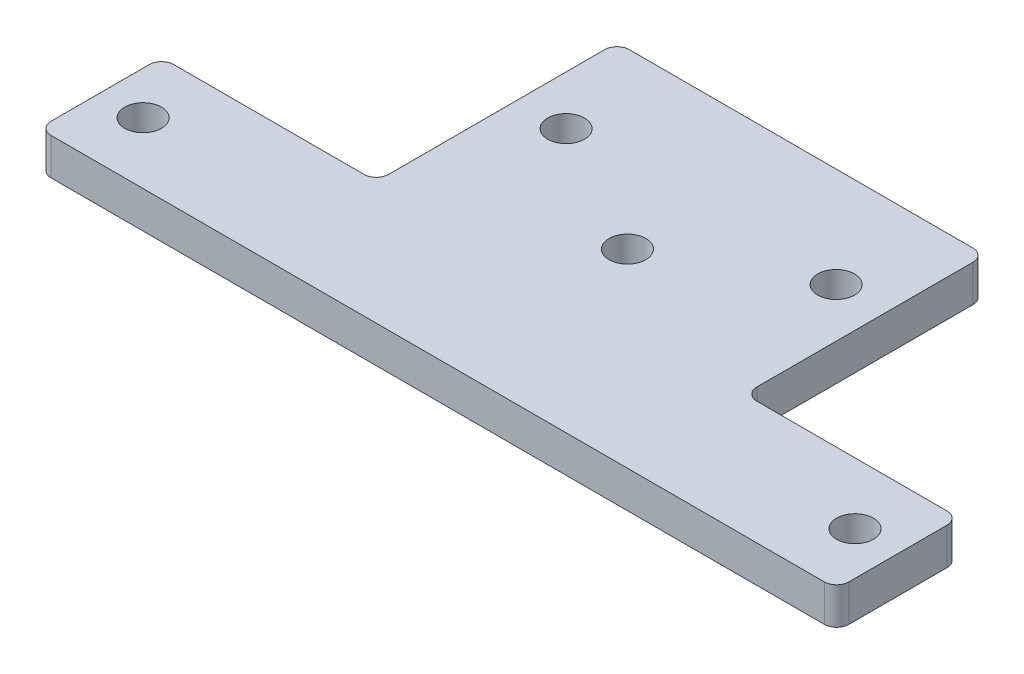
SolidWorks part; units mm, degrees
ref_plane "Alzado" through (0, 0, 0) normal (0, 0, 1) x (1, 0, 0)
ref_plane "Planta" through (0, 0, 0) normal (0, 1, 0) x (1, 0, 0)
ref_plane "Vista lateral" through (0, 0, 0) normal (1, 0, 0) x (0, 0, -1)
sketch "Croquis1" plane through (0, 0, 0) normal (0, 1, 0) x (1, 0, 0)
  line L0 (32.8028, -15.0723) -> (32.8028, -5.0723)
  line L1 (-32.1972, -15.0723) -> (32.8028, -15.0723)
  line L2 (-32.1972, -15.0723) -> (-32.1972, -5.0723)
  line L3 (-14.6972, -5.0723) -> (-14.6972, 14.5371)
  line L4 (-14.6972, 14.5371) -> (15.3028, 14.5371)
  line L5 (15.3028, 14.5371) -> (15.3028, -5.0723)
  line L6 (-32.1972, -5.0723) -> (-14.6972, -5.0723)
  line L7 (15.3028, -5.0723) -> (32.8028, -5.0723)
  line L8 (-9.1972, 6.3895) -> (9.8028, 6.3895) construction
  line L9 (-10.6972, 6.3895) -> (-10.6972, 0.3895) construction
  line L10 (-14.6972, 13.8895) -> (15.3028, 13.8895) construction
  line L11 (-14.6972, 13.8895) -> (-14.6972, -1.1105) construction
  line L13 (15.3028, 13.8895) -> (15.3028, -1.1105) construction
  line L14 (-14.6972, 13.8895) -> (15.3028, -1.1105) construction
  line L15 (-14.6972, -1.1105) -> (15.3028, 13.8895) construction
  line L16 (-10.6972, 0.3895) -> (0.3028, 0.3895) construction
  circle A0 centre (29.3028, -10.0723) radius 1.5
  circle A1 centre (-28.6972, -10.0723) radius 1.5
  circle A2 centre (-10.6972, 6.3895) radius 1.5
  circle A3 centre (11.3028, 6.3895) radius 1.5
  circle A5 centre (0.3028, 0.3895) radius 1.5
  point P18 (0.3028, 6.3895)
  point P19 (0.3028, 14.5371)
  point P20 (0.3028, 6.3895)
  dimension "D5" = 3.5
  dimension "D8" = 3
  dimension "D1" = 17.5
  dimension "D2" = 17.5
  dimension "D3" = 65
  dimension "D4" = 30
  dimension "D6" = 3.5
  dimension "D7" = 22
  dimension "D9" = 15
  dimension "D10" = 30
  dimension "D11" = 6
extrude "Saliente-Extruir1" add sketch "Croquis1" along normal blind 3
fillet "Redondeo1" radius 1 8 edges at (-14.6972, 1.5, 5.0723) (-32.1972, 1.5, 5.0723) (-32.1972, 1.5, 15.0723) (32.8028, 1.5, 15.0723) (15.3028, 1.5, 5.0723) (32.8028, 1.5, 5.0723) (15.3028, 1.5, -14.5371) (-14.6972, 1.5, -14.5371)
